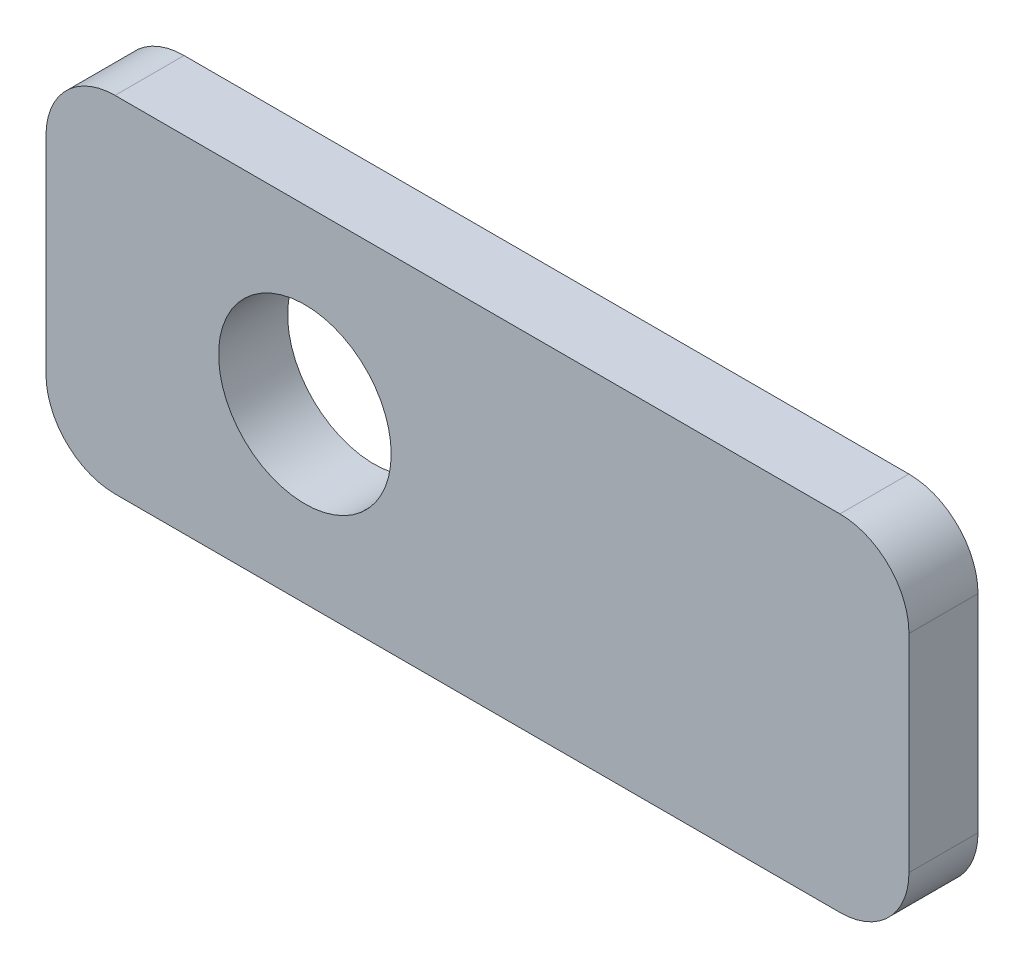
SolidWorks part; units mm, degrees
ref_plane "Front Plane" through (0, 0, 0) normal (0, 0, 1) x (1, 0, 0)
ref_plane "Top Plane" through (0, 0, 0) normal (0, 1, 0) x (1, 0, 0)
ref_plane "Right Plane" through (0, 0, 0) normal (1, 0, 0) x (0, 0, -1)
sketch "Sketch1" plane through (0, 0, 0) normal (0, 0, 1) x (1, 0, 0)
  line L1 (2.54, 0) -> (29.21, 0)
  line L2 (0, 2.54) -> (0, 10.16)
  line L3 (2.54, 12.7) -> (29.21, 12.7)
  line L4 (31.75, 2.54) -> (31.75, 10.16)
  arc A0 (29.21, 0) -> (31.75, 2.54) centre (29.21, 2.54) ccw
  arc A1 (29.21, 12.7) -> (31.75, 10.16) centre (29.21, 10.16) cw
  arc A2 (2.54, 0) -> (0, 2.54) centre (2.54, 2.54) cw
  arc A3 (0, 10.16) -> (2.54, 12.7) centre (2.54, 10.16) cw
  circle A4 centre (9.525, 6.35) radius 3.175
  point P9 (31.75, 12.7)
  point P12 (0, 0)
  point P15 (0, 12.7)
  dimension "D3" = 2.54
  dimension "D4" = 6.35
  dimension "D1" = 12.7
  dimension "D2" = 31.75
  dimension "D5" = 6.35
  dimension "D6" = 9.525
extrude "Boss-Extrude1" add sketch "Sketch1" along normal blind 2.54
